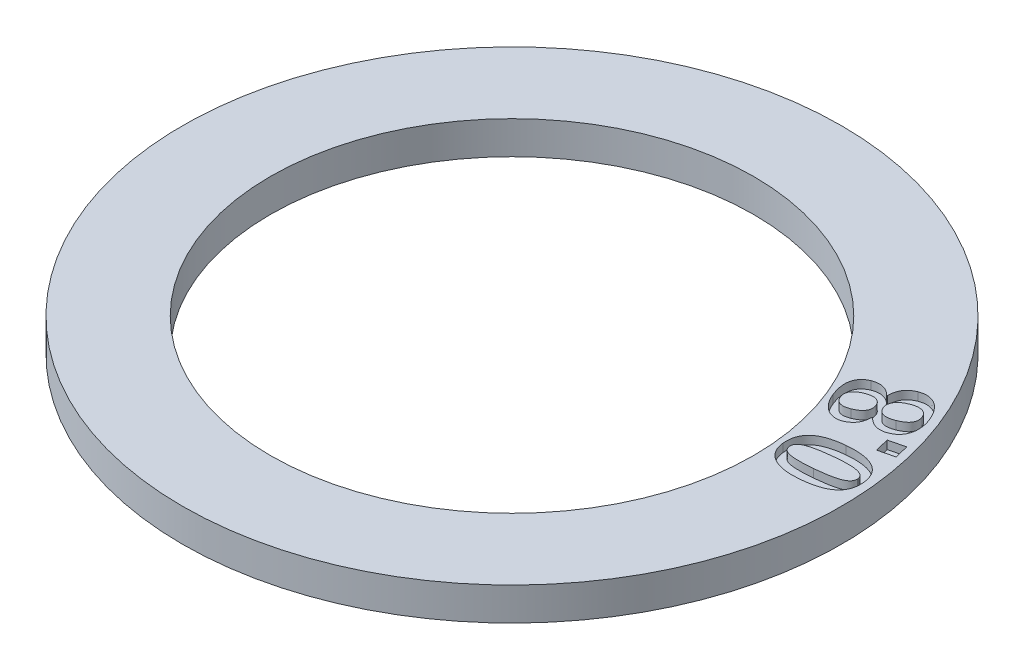
SolidWorks part; units mm, degrees
ref_plane "Front Plane" through (0, 0, 0) normal (0, 0, 1) x (1, 0, 0)
ref_plane "Top Plane" through (0, 0, 0) normal (0, 1, 0) x (1, 0, 0)
ref_plane "Right Plane" through (0, 0, 0) normal (1, 0, 0) x (0, 0, -1)
sketch "Sketch1" plane through (0, 0, 0) normal (0, 1, 0) x (1, 0, 0)
  circle A0 centre (0, 0) radius 8.001
  dimension "D1" = 16.002
extrude "Boss-Extrude1" add sketch "Sketch1" along normal blind 0.8
sketch "Sketch2" plane through (0, 0, 0) normal (0, -1, 0) x (-1, 0, 0)
  circle A0 centre (0, 0) radius 5.8674
  dimension "D1" = 11.7348
extrude "Cut-Extrude1" cut sketch "Sketch2" against normal through all
sketch "Sketch4" plane through (0, 0.8, 0) normal (0, 1, 0) x (1, 0, 0)
  circle A0 centre (0, 0) radius 7.8193 construction
  text T0 "<b>0.8</b>" font "Cambria" height 1.778
extrude "Cut-Extrude2" cut sketch "Sketch4" against normal blind 0.2
